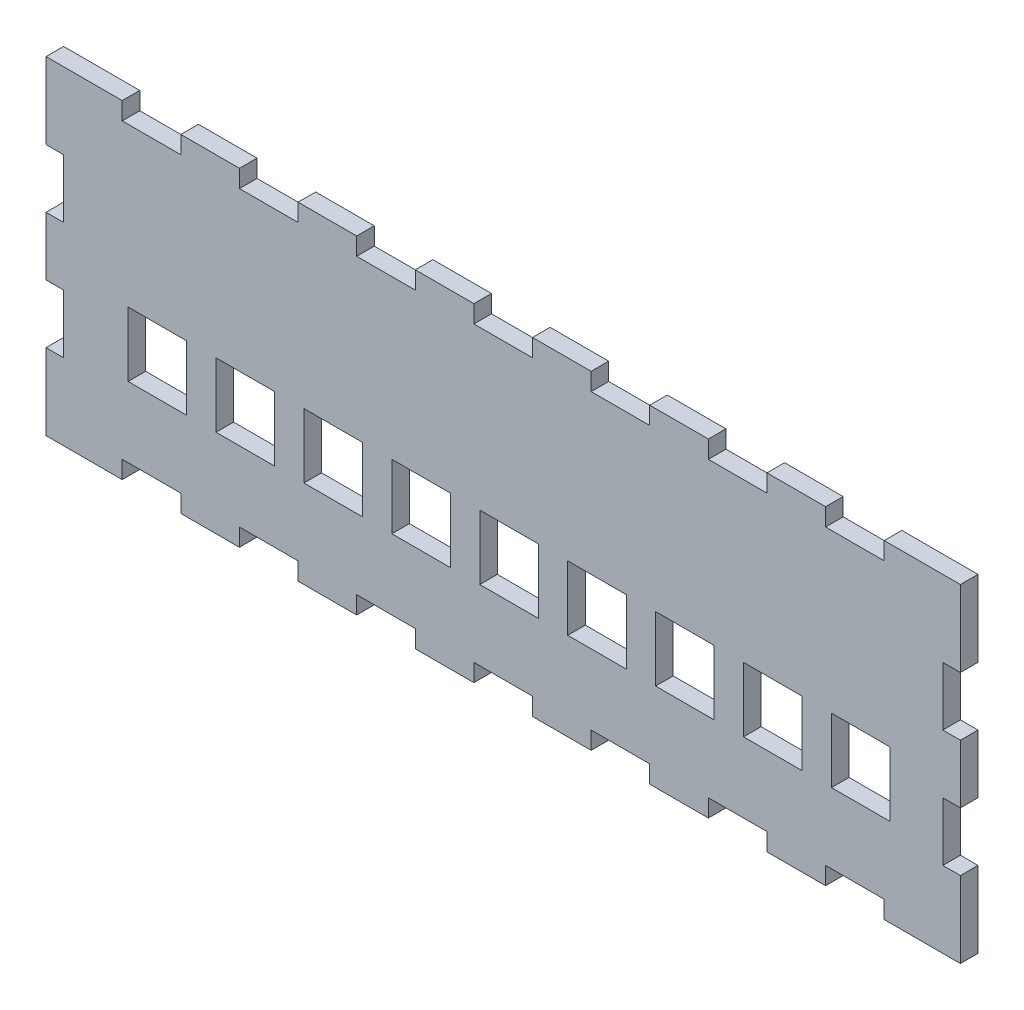
SolidWorks part; units mm, degrees
ref_plane "Front Plane" through (0, 0, 0) normal (0, 0, 1) x (1, 0, 0)
ref_plane "Top Plane" through (0, 0, 0) normal (0, 1, 0) x (1, 0, 0)
ref_plane "Right Plane" through (0, 0, 0) normal (1, 0, 0) x (0, 0, -1)
sketch "Sketch1" plane through (0, 0, 0) normal (0, 0, 1) x (1, 0, 0)
  line L0 (15, 28) -> (15, 25)
  line L1 (-76.5, 26.5) -> (76.5, 26.5) construction
  line L2 (-76.5, 26.5) -> (-76.5, -26.5) construction
  line L3 (-76.5, -26.5) -> (76.5, -26.5) construction
  line L4 (76.5, 26.5) -> (76.5, -26.5) construction
  line L5 (-76.5, 26.5) -> (76.5, -26.5) construction
  line L6 (-76.5, -26.5) -> (76.5, 26.5) construction
  line L7 (-5, 28) -> (5, 28) construction
  line L8 (-5, 28) -> (-5, 25)
  line L9 (-5, 25) -> (5, 25)
  line L10 (5, 28) -> (5, 25)
  line L11 (-5, 28) -> (5, 25) construction
  line L12 (-5, 25) -> (5, 28) construction
  line L13 (15, 25) -> (25, 25)
  line L14 (25, 28) -> (25, 25)
  line L15 (35, 28) -> (35, 25)
  line L16 (35, 25) -> (45, 25)
  line L17 (45, 28) -> (45, 25)
  line L18 (55, 28) -> (55, 25)
  line L19 (55, 25) -> (65, 25)
  line L20 (65, 28) -> (65, 25)
  line L21 (5, 28) -> (15, 28)
  line L22 (25, 28) -> (35, 28)
  line L23 (45, 28) -> (55, 28)
  line L24 (65, 28) -> (78, 28)
  line L25 (-25, 25) -> (-15, 25)
  line L26 (-25, 28) -> (-25, 25)
  line L27 (-15, 28) -> (-15, 25)
  line L28 (-45, 25) -> (-35, 25)
  line L29 (-45, 28) -> (-45, 25)
  line L30 (-35, 28) -> (-35, 25)
  line L31 (-65, 25) -> (-55, 25)
  line L32 (-65, 28) -> (-65, 25)
  line L33 (-55, 28) -> (-55, 25)
  line L34 (-55, 28) -> (-45, 28)
  line L35 (-35, 28) -> (-25, 28)
  line L36 (-15, 28) -> (-5, 28)
  line L37 (-65, 28) -> (-78, 28)
  line L38 (0, 0) -> (10.7491, 0) construction
  line L39 (0, 0) -> (0, 9.6256) construction
  line L40 (65, -28) -> (78, -28)
  line L41 (65, -28) -> (65, -25)
  line L42 (55, -25) -> (65, -25)
  line L43 (55, -28) -> (55, -25)
  line L44 (45, -28) -> (55, -28)
  line L45 (45, -28) -> (45, -25)
  line L46 (35, -25) -> (45, -25)
  line L47 (35, -28) -> (35, -25)
  line L48 (25, -28) -> (35, -28)
  line L49 (25, -28) -> (25, -25)
  line L50 (15, -25) -> (25, -25)
  line L51 (15, -28) -> (15, -25)
  line L52 (5, -28) -> (15, -28)
  line L53 (5, -28) -> (5, -25)
  line L54 (-5, -25) -> (5, -25)
  line L55 (-5, -28) -> (-5, -25)
  line L56 (-15, -28) -> (-5, -28)
  line L57 (-15, -28) -> (-15, -25)
  line L58 (-25, -25) -> (-15, -25)
  line L59 (-25, -28) -> (-25, -25)
  line L60 (-35, -28) -> (-25, -28)
  line L61 (-35, -28) -> (-35, -25)
  line L62 (-45, -25) -> (-35, -25)
  line L63 (-45, -28) -> (-45, -25)
  line L64 (-55, -28) -> (-45, -28)
  line L65 (-55, -28) -> (-55, -25)
  line L66 (-65, -25) -> (-55, -25)
  line L67 (-65, -28) -> (-65, -25)
  line L68 (-65, -28) -> (-78, -28)
  line L69 (78, 28) -> (78, 15)
  line L70 (78, -28) -> (78, -15)
  line L71 (75, -5) -> (78, -5)
  line L72 (75, -5) -> (75, -15)
  line L73 (75, -15) -> (78, -15)
  line L74 (78, -5) -> (78, -15) construction
  line L75 (75, -5) -> (78, -15) construction
  line L76 (75, -15) -> (78, -5) construction
  line L77 (75, 15) -> (75, 5)
  line L78 (75, 15) -> (78, 15)
  line L79 (75, 5) -> (78, 5)
  line L80 (78, -5) -> (78, 5)
  line L81 (-78, -28) -> (-78, -15)
  line L82 (-75, -15) -> (-78, -15)
  line L83 (-75, -5) -> (-75, -15)
  line L84 (-75, -5) -> (-78, -5)
  line L85 (-78, -5) -> (-78, 5)
  line L86 (-75, 5) -> (-78, 5)
  line L87 (-75, 15) -> (-75, 5)
  line L88 (-75, 15) -> (-78, 15)
  line L89 (-78, 28) -> (-78, 15)
  point P0 (0, 0)
  point P6 (0, 26.5)
  point P70 (76.5, -10)
  dimension "D1" = 153
  dimension "D2" = 53
  dimension "D3" = 10
  dimension "D4" = 3
  dimension "D7" = 10
  dimension "D9" = 10
  dimension "D10" = 13
  dimension "D11" = 10
  dimension "D12" = 13
  dimension "D13" = 13
  dimension "D5" = 4
  dimension "D8" = 4
  dimension "D14" = 2
extrude "Boss-Extrude1" add sketch "Sketch1" along normal blind 3
sketch "Sketch4" plane through (0, 0, 0) normal (0, 0, -1) x (-1, 0, 0)
  line L0 (-78, -13) -> (78, -13) construction
  line L1 (5, -25) -> (-5, -25) construction
  line L2 (-78, -28) -> (-78, -15) construction
  line L3 (78, -15) -> (78, -28) construction
  line L4 (0, -13) -> (0, 0) construction
  line L5 (-74, -13) -> (-74, -7) construction
  line L6 (-66, -13) -> (-56, -13)
  line L7 (-66, -13) -> (-66, -2)
  line L8 (-66, -2) -> (-56, -2)
  line L9 (-56, -13) -> (-56, -2)
  line L10 (-51, -13) -> (-51, -2)
  line L23 (-51, -13) -> (-41, -13)
  line L24 (-41, -13) -> (-41, -2)
  line L25 (-51, -2) -> (-41, -2)
  line L26 (-36, -13) -> (-36, -2)
  line L27 (-36, -13) -> (-26, -13)
  line L28 (-26, -13) -> (-26, -2)
  line L29 (-36, -2) -> (-26, -2)
  line L30 (-21, -13) -> (-21, -2)
  line L31 (-21, -13) -> (-11, -13)
  line L32 (-11, -13) -> (-11, -2)
  line L33 (-21, -2) -> (-11, -2)
  line L34 (-6, -13) -> (-6, -2)
  line L35 (-6, -13) -> (4, -13)
  line L36 (4, -13) -> (4, -2)
  line L37 (-6, -2) -> (4, -2)
  line L38 (9, -13) -> (9, -2)
  line L39 (9, -13) -> (19, -13)
  line L40 (19, -13) -> (19, -2)
  line L41 (9, -2) -> (19, -2)
  line L42 (24, -13) -> (24, -2)
  line L43 (24, -13) -> (34, -13)
  line L44 (34, -13) -> (34, -2)
  line L45 (24, -2) -> (34, -2)
  line L46 (39, -13) -> (39, -2)
  line L47 (39, -13) -> (49, -13)
  line L48 (49, -13) -> (49, -2)
  line L49 (39, -2) -> (49, -2)
  line L50 (54, -13) -> (54, -2)
  line L51 (54, -13) -> (64, -13)
  line L52 (64, -13) -> (64, -2)
  line L53 (54, -2) -> (64, -2)
  dimension "D1" = 12
  dimension "D2" = 11
  dimension "D3" = 10
  dimension "D4" = 8
  dimension "D5" = 74
  dimension "D6" = 9
  dimension "D7" = 5
extrude "Cut-Extrude2" cut sketch "Sketch4" against normal blind 3
